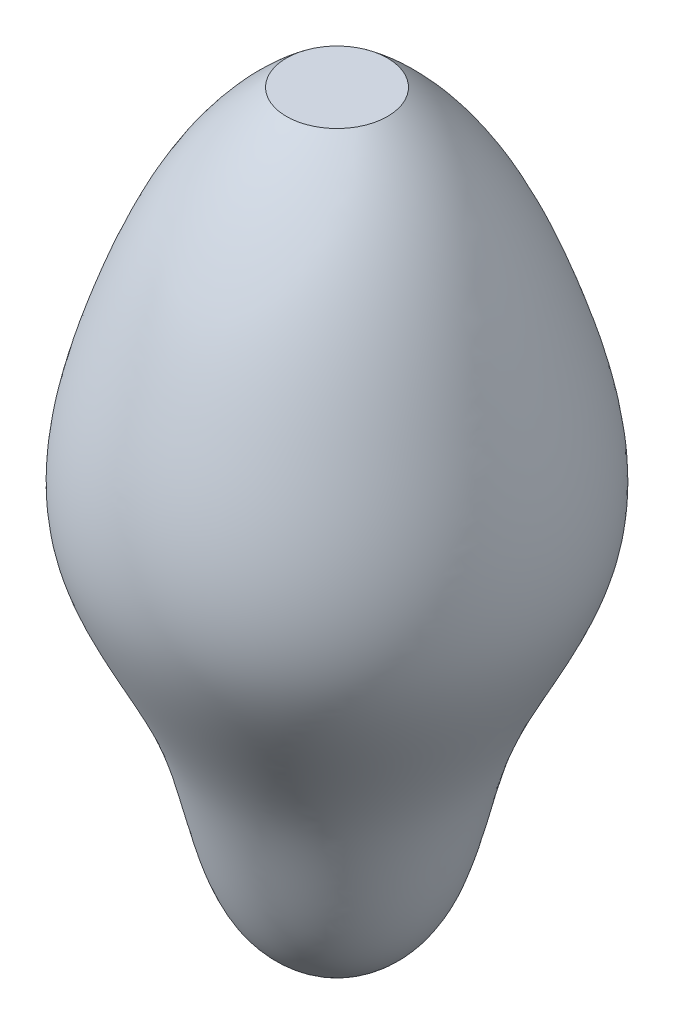
SolidWorks part; units mm, degrees
ref_plane "前视基准面" through (0, 0, 0) normal (0, 0, 1) x (1, 0, 0)
ref_plane "上视基准面" through (0, 0, 0) normal (0, 1, 0) x (1, 0, 0)
ref_plane "右视基准面" through (0, 0, 0) normal (1, 0, 0) x (0, 0, -1)
other "Configuration Table"
sketch "草图1" plane through (0, 0, 0) normal (0, 0, 1) x (1, 0, 0)
  line L0 (0, 0) -> (0, 300) construction
  line L1 (20, 300) -> (0, 300)
  line L2 (0, 0) -> (0, 300)
  spline S0 degree 3 poles (0, 0) (40.5079, 9.4058) (37.0248, 77.0594) (90.9853, 145.7703) (69.3766, 230.0016) (45.8677, 279.8725) (20, 300) knots 0 0 0 0 0.290749 0.513735 0.720772 1 1 1 1
revolve "旋转1" add sketch "草图1" angle 360 about L0
